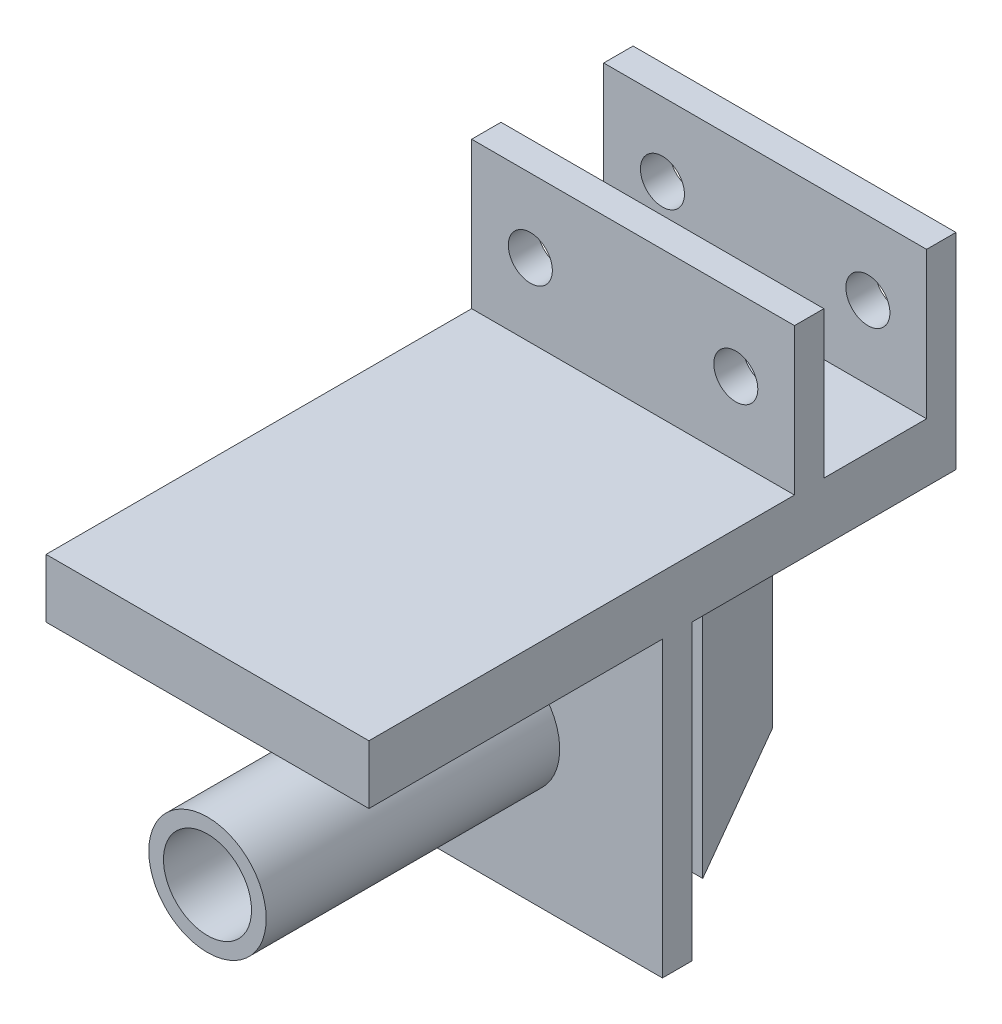
SolidWorks part; units mm, degrees
ref_plane "Спереди" through (0, 0, 0) normal (0, 0, 1) x (1, 0, 0)
ref_plane "Сверху" through (0, 0, 0) normal (0, 1, 0) x (1, 0, 0)
ref_plane "Справа" through (0, 0, 0) normal (1, 0, 0) x (0, 0, -1)
sketch "Эскиз2" plane through (0, 0, 0) normal (0, 1, 0) x (1, 0, 0)
  line L1 (-45.832, 9.5584) -> (-23.832, 9.5584)
  line L2 (-45.832, 9.5584) -> (-45.832, -30.4416)
  line L3 (-45.832, -30.4416) -> (-23.832, -30.4416)
  line L4 (-23.832, 9.5584) -> (-23.832, -30.4416)
extrude "Бобышка-Вытянуть1" add sketch "Эскиз2" along normal blind 4
sketch "Эскиз3" plane through (0, 4, 0) normal (0, 1, 0) x (1, 0, 0)
  line L0 (-23.832, -30.4416) -> (-23.832, 9.5584) construction
  line L1 (-45.832, 9.5584) -> (-23.832, 9.5584)
  line L2 (-45.832, 9.5584) -> (-45.832, 7.5584)
  line L3 (-45.832, 7.5584) -> (-23.832, 7.5584)
  line L4 (-23.832, 9.5584) -> (-23.832, 7.5584)
  line L5 (-45.832, 0.5584) -> (-23.832, 0.5584)
  line L6 (-45.832, 9.5584) -> (-45.832, -30.4416) construction
  line L7 (-45.832, -1.4416) -> (-23.832, -1.4416)
  line M4 (-45.832, 9.5584) -> (-45.832, -30.4416)
  line M6 (-23.832, -30.4416) -> (-23.832, 9.5584)
  line M7 (-23.832, 9.5584) -> (-45.832, 9.5584)
  dimension "D1" = 7
  dimension "D2" = 2
  dimension "D3" = 2
extrude "Бобышка-Вытянуть2" add sketch "Эскиз3" along normal blind 10 contours L3 M4 M6 M7 | L7 L5 M4 M6
sketch "Эскиз4" plane through (0, 0, 1.4416) normal (0, 0, 1) x (1, 0, 0)
  line L0 (-34.832, 4) -> (-34.832, 14) construction
  line L1 (-45.832, 4) -> (-23.832, 4) construction
  line L2 (-45.832, 14) -> (-23.832, 14) construction
  line L3 (-45.832, 9) -> (-23.832, 9) construction
  line L4 (-45.832, 14) -> (-45.832, 4) construction
  line L5 (-23.832, 14) -> (-23.832, 4) construction
  line L6 (-41.832, 14) -> (-41.832, 4) construction
  line L7 (-45.832, 4) -> (-23.832, 4) construction
  line L8 (-27.832, 14) -> (-27.832, 4) construction
  circle A0 centre (-41.832, 9) radius 1.5
  circle A1 centre (-27.832, 9) radius 1.5
  dimension "D1" = 5
  dimension "D2" = 7
  dimension "D3" = 7
extrude "Вырез-Вытянуть1" cut sketch "Эскиз4" against normal blind 11
sketch "Эскиз5" plane through (0, 0, 0) normal (0, -1, 0) x (1, 0, 0)
  line L0 (-34.4299, 30.4416) -> (-34.4299, -9.5584) construction
  line L1 (-45.832, 30.4416) -> (-23.832, 30.4416) construction
  line L2 (-23.832, -9.5584) -> (-45.832, -9.5584) construction
  line L3 (-45.832, 10.4416) -> (-23.832, 10.4416) construction
  line L4 (-45.832, -9.5584) -> (-45.832, 30.4416) construction
  line L5 (-23.832, 30.4416) -> (-23.832, -9.5584) construction
  line L6 (-23.832, 8.4416) -> (-45.832, 8.4416) construction
  line L8 (-45.832, 10.4416) -> (-23.832, 10.4416)
  line L9 (-45.832, 10.4416) -> (-45.832, 8.4416)
  line L10 (-45.832, 8.4416) -> (-23.832, 8.4416)
  line L11 (-23.832, 10.4416) -> (-23.832, 8.4416)
  dimension "D1" = 18
  dimension "D2" = 2
extrude "Бобышка-Вытянуть3" add sketch "Эскиз5" along normal blind 20
sketch "Эскиз6" plane through (0, 0, 10.4416) normal (0, 0, 1) x (1, 0, 0)
  line L0 (-34.832, 0) -> (-34.832, -20) construction
  line L1 (-23.832, 0) -> (-45.832, 0) construction
  line L2 (-23.832, -20) -> (-45.832, -20) construction
  line L3 (-45.832, -10) -> (-23.832, -10) construction
  line L4 (-45.832, -20) -> (-45.832, 0) construction
  line L5 (-23.832, -20) -> (-23.832, 0) construction
  circle A0 centre (-34.832, -10) radius 4
  circle A1 centre (-34.832, -10) radius 3
  dimension "D1" = 10
  dimension "D2" = 6
extrude "Бобышка-Вытянуть4" add sketch "Эскиз6" along normal blind 20
sketch "Эскиз8" plane through (0, 0, 0) normal (0, -1, 0) x (1, 0, 0)
  line L0 (-34.832, 8.4416) -> (-34.832, -9.5584) construction
  line L1 (-45.832, 8.4416) -> (-23.832, 8.4416) construction
  line L2 (-23.832, -9.5584) -> (-45.832, -9.5584) construction
  line L3 (-45.832, -0.5584) -> (-23.832, -0.5584) construction
  line L4 (-45.832, -9.5584) -> (-45.832, 8.4416) construction
  line L5 (-23.832, 8.4416) -> (-23.832, -9.5584) construction
  line L7 (-34.832, -8.0639) -> (-28.332, 3.1944)
  line L8 (-28.332, 3.1944) -> (-41.332, 3.1944)
  line L9 (-41.332, 3.1944) -> (-34.832, -8.0639)
  circle A0 centre (-34.832, -0.5584) radius 3.7528 construction
extrude "Бобышка-Вытянуть6" add sketch "Эскиз8" along normal blind 20
